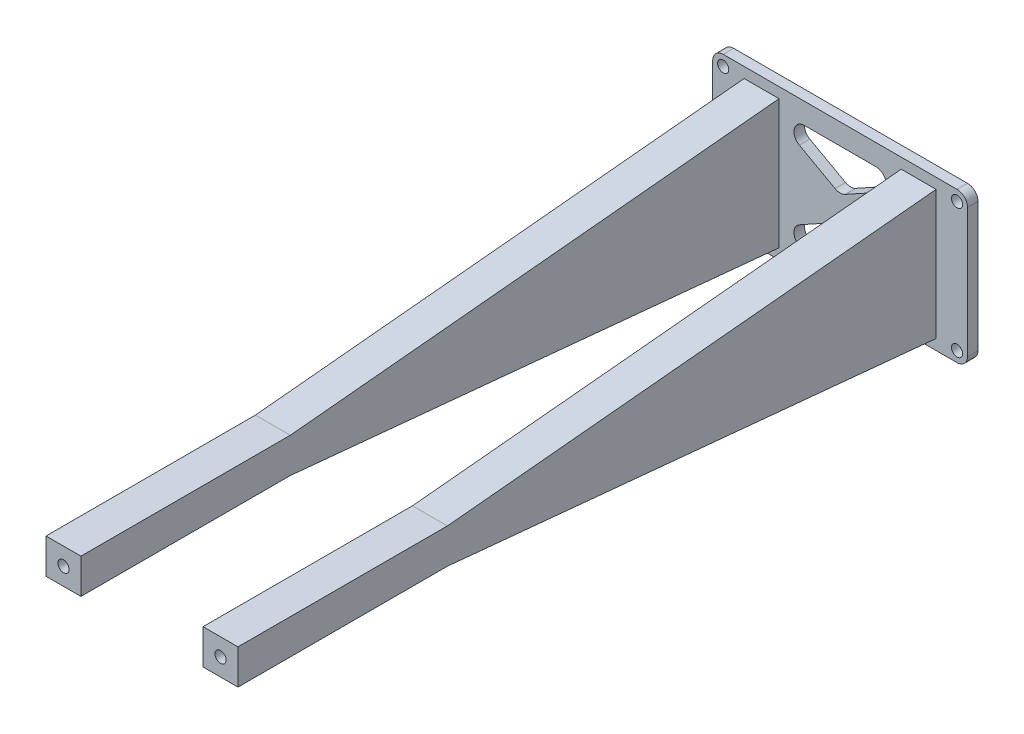
SolidWorks part; units mm, degrees
ref_plane "前视基准面" through (0, 0, 0) normal (0, 0, 1) x (1, 0, 0)
ref_plane "上视基准面" through (0, 0, 0) normal (0, 1, 0) x (1, 0, 0)
ref_plane "右视基准面" through (0, 0, 0) normal (1, 0, 0) x (0, 0, -1)
sketch "草图1" plane through (0, 0, 0) normal (0, 0, 1) x (1, 0, 0)
  line L7 (1.4503, -4.2279) -> (11.6739, -9.8738)
  line L8 (11.6739, 9.8738) -> (1.4503, 4.2279)
  line L9 (33.5, 21.5) -> (-33.5, 21.5)
  line L10 (-33.5, -21.5) -> (33.5, -21.5)
  line L13 (36.5, -18.5) -> (36.5, 18.5)
  line L14 (-11.6739, 9.8738) -> (-1.4503, 4.2279)
  line L15 (-1.4503, -4.2279) -> (-11.6739, -9.8738)
  line L16 (10.2236, 15.5) -> (-10.2236, 15.5)
  line L17 (-10.2236, -15.5) -> (10.2236, -15.5)
  line L19 (-36.5, -18.5) -> (-36.5, 18.5)
  circle A0 centre (33.5, 18.5) radius 1.6
  circle A1 centre (-33.5, 18.5) radius 1.6
  circle A2 centre (33.5, -18.5) radius 1.6
  circle A3 centre (-33.5, -18.5) radius 1.6
  arc A5 (-10.2236, -15.5) -> (-11.6739, -9.8738) centre (-10.2236, -12.5) cw
  arc A6 (10.2236, -15.5) -> (11.6739, -9.8738) centre (10.2236, -12.5) ccw
  arc A8 (11.6739, 9.8738) -> (10.2236, 15.5) centre (10.2236, 12.5) ccw
  arc A9 (-11.6739, 9.8738) -> (-10.2236, 15.5) centre (-10.2236, 12.5) cw
  arc A11 (-36.5, -18.5) -> (-33.5, -21.5) centre (-33.5, -18.5) ccw
  arc A12 (33.5, -21.5) -> (36.5, -18.5) centre (33.5, -18.5) ccw
  arc A13 (36.5, 18.5) -> (33.5, 21.5) centre (33.5, 18.5) ccw
  arc A14 (-33.5, 21.5) -> (-36.5, 18.5) centre (-33.5, 18.5) ccw
  arc A15 (1.4503, 4.2279) -> (-1.4503, 4.2279) centre (0, 6.8541) cw
  arc A16 (1.4503, -4.2279) -> (-1.4503, -4.2279) centre (0, -6.8541) ccw
  dimension "D4" = 3
extrude "凸台-拉伸1" add sketch "草图1" along normal blind 3
sketch "草图2" plane through (0, 0, 3) normal (0, 0, 1) x (1, 0, 0)
  line L1 (-27.5, 5) -> (-17.5, 5)
  line L2 (-27.5, 5) -> (-27.5, -5)
  line L3 (-27.5, -5) -> (-17.5, -5)
  line L4 (-17.5, 5) -> (-17.5, -5)
  line L5 (-27.5, 5) -> (-17.5, -5) construction
  line L6 (-27.5, -5) -> (-17.5, 5) construction
  line L7 (17.5, 5) -> (27.5, 5)
  line L8 (17.5, 5) -> (17.5, -5)
  line L9 (17.5, -5) -> (27.5, -5)
  line L10 (27.5, 5) -> (27.5, -5)
  line L11 (17.5, 5) -> (27.5, -5) construction
  line L12 (17.5, -5) -> (27.5, 5) construction
  point P0 (0, 0)
  point P12 (0, 0)
  point P13 (0, 0)
  point P14 (0, 0)
extrude "凸台-拉伸3" add sketch "草图2" along normal blind 140
sketch "草图5" plane through (-27.5, 0, 0) normal (-1, 0, 0) x (0, 0, 1)
  line L0 (3, 18.5) -> (3, 5)
  line L1 (3, 5) -> (143, 5)
  line L2 (143, 5) -> (3, 18.5)
extrude "凸台-拉伸4" add sketch "草图5" against normal blind 10
sketch "草图6" plane through (-27.5, 0, 0) normal (-1, 0, 0) x (0, 0, 1)
  line L0 (3, -5) -> (3, -18.5)
  line L1 (3, -18.5) -> (143, -5)
  line L2 (143, -5) -> (3, -5)
extrude "凸台-拉伸5" add sketch "草图6" against normal blind 10
sketch "草图7" plane through (27.5, 0, 0) normal (1, 0, 0) x (0, 0, -1)
  line L0 (-143, 5) -> (-3, 5)
  line L1 (-3, 5) -> (-3, 18.5)
  line L2 (-3, 18.5) -> (-143, 5)
  line L3 (-143, -5) -> (-3, -18.5)
  line L4 (-3, -18.5) -> (-3, -5)
  line L5 (-3, -5) -> (-143, -5)
extrude "凸台-拉伸6" add sketch "草图7" against normal blind 10
sketch "草图9" plane through (0, 0, 143) normal (0, 0, 1) x (1, 0, 0)
  line L1 (-27.5, 5) -> (-17.5, 5)
  line L2 (-27.5, 5) -> (-27.5, -5)
  line L3 (-27.5, -5) -> (-17.5, -5)
  line L4 (-17.5, 5) -> (-17.5, -5)
extrude "凸台-拉伸7" add sketch "草图9" along normal blind 60
sketch "草图10" plane through (0, 0, 143) normal (0, 0, 1) x (1, 0, 0)
  line L1 (17.5, 5) -> (27.5, 5)
  line L2 (17.5, 5) -> (17.5, -5)
  line L3 (17.5, -5) -> (27.5, -5)
  line L4 (27.5, 5) -> (27.5, -5)
extrude "凸台-拉伸8" add sketch "草图10" along normal blind 60
sketch "草图11" plane through (0, 0, 203) normal (0, 0, 1) x (1, 0, 0)
  circle A0 centre (-22.5, 0) radius 1.6
extrude "切除-拉伸3" cut sketch "草图11" against normal blind 20
sketch "草图12" plane through (0, 0, 203) normal (0, 0, 1) x (1, 0, 0)
  circle A0 centre (22.5, 0) radius 1.6
extrude "切除-拉伸4" cut sketch "草图12" against normal blind 20
